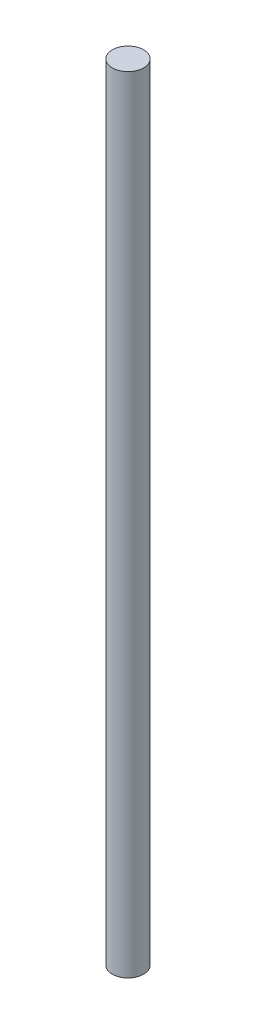
SolidWorks part; units mm, degrees
material "3.0517 (EN-AW 3003)"
ref_plane "前视基准面" through (0, 0, 0) normal (0, 0, 1) x (1, 0, 0)
ref_plane "上视基准面" through (0, 0, 0) normal (0, 1, 0) x (1, 0, 0)
ref_plane "右视基准面" through (0, 0, 0) normal (1, 0, 0) x (0, 0, -1)
sketch "草图1" plane through (0, 0, 0) normal (0, 1, 0) x (1, 0, 0)
  circle A0 centre (0, 0) radius 2
extrude "凸台-拉伸1" add sketch "草图1" along normal blind 100
